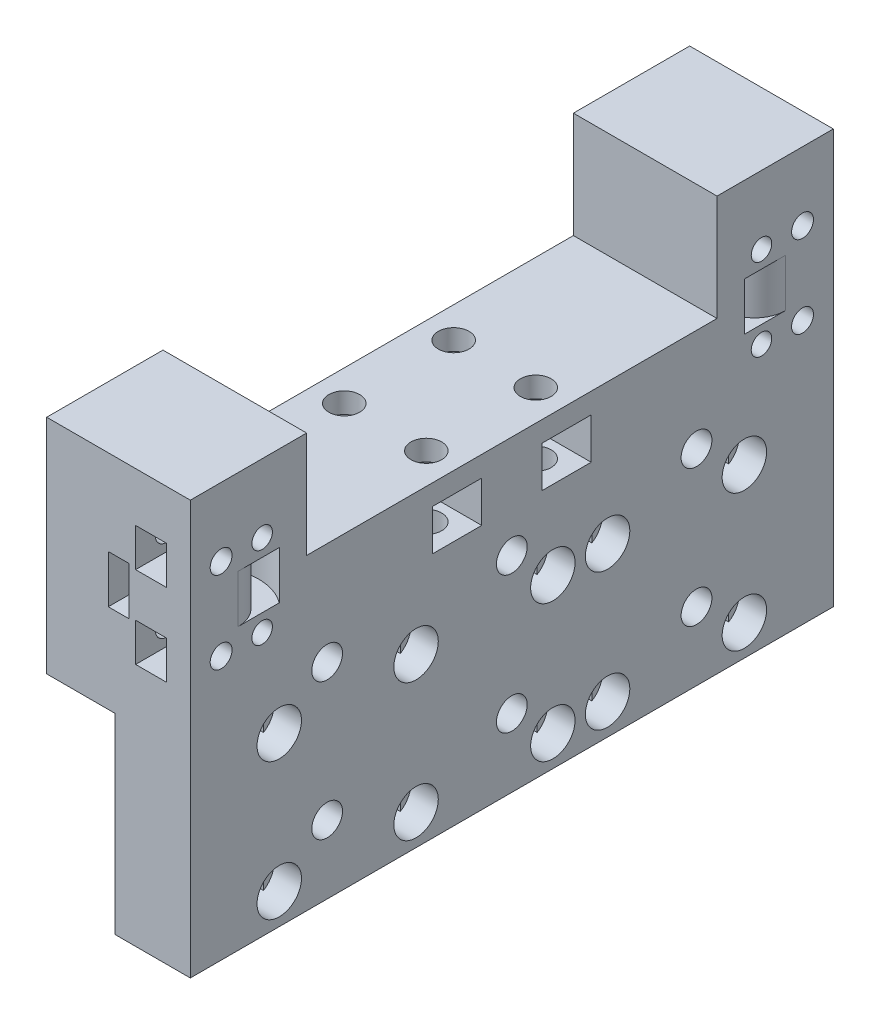
SolidWorks part; units mm, degrees
material "3D printed plastic"
ref_plane "Front Plane" through (0, 0, 0) normal (0, 0, 1) x (1, 0, 0)
ref_plane "Top Plane" through (0, 0, 0) normal (0, 1, 0) x (1, 0, 0)
ref_plane "Right Plane" through (0, 0, 0) normal (1, 0, 0) x (0, 0, -1)
sketch "Sketch1" plane through (0, 0, 0) normal (0, 0, 1) x (1, 0, 0)
  line L1 (0, 0) -> (11, 0)
  line L2 (0, 0) -> (0, 28)
  line L4 (11, 0) -> (11, 60.5)
  line L5 (0, 28) -> (-10, 28)
  line L7 (11, 60.5) -> (-10, 60.5)
  line L8 (-10, 28) -> (-10, 60.5)
  dimension "D1" = 28
  dimension "D2" = 10
  dimension "D4" = 32.5
  dimension "D6" = 11
extrude "Boss-Extrude1" add sketch "Sketch1" along normal mid plane 94
hole_wizard "CBORE for M3 Hex Socket Head Cap Screw1" positions "Sketch3" profile "Sketch2" counterbore size "M3" standard "DIN" end condition through all
sketch "Sketch3" plane through (11, 0, 0) normal (1, 0, 0) x (0, 0, -1)
  line L0 (-34, 24.5) -> (-34, 4.5) construction
  line L1 (-34, 4.5) -> (-14, 4.5) construction
  line L2 (-14, 4.5) -> (-14, 24.5) construction
  line L3 (-14, 24.5) -> (-34, 24.5) construction
  line L5 (0, 0) -> (0, 16.7465) construction
  line L7 (14, 24.5) -> (34, 24.5) construction
  line L8 (14, 4.5) -> (14, 24.5) construction
  line L9 (34, 4.5) -> (14, 4.5) construction
  line L10 (34, 24.5) -> (34, 4.5) construction
  line L11 (-34, 14.5) -> (-14, 14.5) construction
  line L16 (-24, 14.5) -> (-24, 4.5) construction
  line L19 (-47, 0) -> (47, 0) construction
  line L20 (6, 24.5) -> (-14, 24.5) construction
  line L22 (6, 24.5) -> (6, 4.5) construction
  line L23 (6, 4.5) -> (-14, 4.5) construction
  point P0 (-34, 4.5)
  point P2 (-34, 24.5)
  point P4 (-14, 24.5)
  point P6 (-14, 4.5)
  point P21 (14, 24.5)
  point P22 (34, 24.5)
  point P23 (14, 4.5)
  point P24 (34, 4.5)
  point P48 (6, 24.5)
  point P50 (6, 4.5)
  dimension "D1" = 20
  dimension "D2" = 48
  dimension "D3" = 14.5
sketch "Sketch2" plane through (11, 4.5, 34) normal (0, 1, 0) x (0, 0, -1)
  line L0 (0, 0) -> (0, 21)
  line L1 (0, 21) -> (1.7, 21)
  line L3 (1.7, 21) -> (1.7, 4)
  line L4 (1.7, 4) -> (3.25, 4)
  line L5 (3.25, 4) -> (3.25, 0)
  line L7 (3.25, 0) -> (0, 0)
  line L11 (0, -6.35) -> (0, 107.95) construction
  dimension "Thru Hole Dia." = 3.4
  dimension "Thru Hole Depth" = 21
  dimension "C'Bore Dia." = 6.5
  dimension "C'Bore Depth" = 4
sketch "Sketch4" plane through (0, 0, 47) normal (0, 0, 1) x (1, 0, 0)
  line L0 (11, 0) -> (11, 60.5) construction
  line L1 (-1, 48) -> (2, 48)
  line L2 (-1, 48) -> (-1, 41)
  line L3 (-1, 41) -> (2, 41)
  line L4 (2, 48) -> (2, 41)
  line L5 (-10, 28) -> (0, 28) construction
  line L6 (-1, 48) -> (2, 41) construction
  line L7 (0.5, 44.5) -> (0.5, 41) construction
  dimension "D1" = 7
  dimension "D2" = 3
  dimension "D3" = 9
  dimension "D4" = 13
ref_plane "Plane1" through (0, 44.5, 0) normal (0, 1, 0) x (1, 0, 0)
sketch "Sketch7" plane through (0, 44.5, 0) normal (0, 1, 0) x (1, 0, 0)
  line L0 (0.5, -47) -> (0.5, -40)
  line L1 (-1, -47) -> (2, -47) construction
  line L2 (12.5, -40) -> (6.5, -40) construction
  arc A1 (0.5, -40) -> (12.5, -40) centre (6.5, -40) cw
  dimension "D1" = 1.5
  dimension "D2" = 7
sweep "Cut-Sweep1" cut profiles "Sketch4" path "Sketch7"
sketch "Sketch8" plane through (11, 0, 0) normal (1, 0, 0) x (0, 0, -1)
  line L0 (-42.5, 38.5) -> (-42.5, 50.5) construction
  line L1 (-42.5, 44.5) -> (-40, 44.5) construction
  line L2 (-40, 41) -> (-40, 48) construction
  line L3 (-47, 0) -> (-47, 60.5) construction
  circle A0 centre (-42.5, 50.5) radius 1.6
  circle A1 centre (-42.5, 38.5) radius 1.6
  dimension "D1" = 12
  dimension "D2" = 3.2
  dimension "D3" = 4.5
extrude "Cut-Extrude1" cut sketch "Sketch8" against normal blind 12
sketch "Sketch10" plane through (11, 0, 0) normal (1, 0, 0) x (0, 0, -1)
  line L0 (-44.1166, 41.3) -> (-47, 41.3)
  line L1 (-47, 44.5) -> (-41.3484, 44.5) construction
  line L2 (-44.1166, 47.7) -> (-45.7332, 50.5) construction
  line L3 (-39.2668, 50.5) -> (-40.8834, 47.7) construction
  line L4 (-40.8834, 53.3) -> (-39.2668, 50.5) construction
  line L5 (-45.7332, 50.5) -> (-44.1166, 53.3) construction
  line L6 (-40.4834, 47.7) -> (-40.8834, 47.7)
  line L7 (-45.7332, 38.5) -> (-44.1166, 35.7) construction
  line L8 (-44.1166, 35.7) -> (-40.8834, 35.7)
  line L9 (-40.8834, 35.7) -> (-39.2668, 38.5) construction
  line L10 (-39.2668, 38.5) -> (-40.8834, 41.3) construction
  line L11 (-40.8834, 41.3) -> (-44.1166, 41.3)
  line L12 (-44.1166, 41.3) -> (-45.7332, 38.5) construction
  line L13 (-47, 0) -> (-47, 60.5) construction
  line L14 (-47, 41.3) -> (-47, 35.7)
  line L15 (-47, 35.7) -> (-44.1166, 35.7)
  line L16 (-40.8834, 35.7) -> (-40.4834, 35.7)
  line L17 (-40.4834, 35.7) -> (-38.8668, 38.5)
  line L18 (-38.8668, 38.5) -> (-40.4834, 41.3)
  line L19 (-40.4834, 41.3) -> (-40.8834, 41.3)
  line L20 (-38.8668, 50.5) -> (-40.4834, 47.7)
  line L21 (-40.4834, 53.3) -> (-38.8668, 50.5)
  line L22 (-40.8834, 53.3) -> (-40.4834, 53.3)
  line L23 (-47, 53.3) -> (-44.1166, 53.3)
  line L24 (-47, 47.7) -> (-47, 53.3)
  line L25 (-40.8834, 47.7) -> (-44.1166, 47.7)
  line L26 (-44.1166, 53.3) -> (-40.8834, 53.3)
  line L27 (-44.1166, 47.7) -> (-47, 47.7)
  circle A0 centre (-42.5, 50.5) radius 2.8 construction
  circle A1 centre (-42.5, 38.5) radius 2.8 construction
  dimension "D1" = 5.6
  dimension "D2" = 0.4
extrude "Cut-Extrude2" cut sketch "Sketch10" against normal blind 4.5 from offset 3.5 offset against normal yes
mirror "Mirror1" about plane through (0, 0, 0) normal (0, 0, 1) of "Cut-Extrude2", "Cut-Extrude1", "Cut-Sweep1"
sketch "Sketch11" plane through (11, 0, 0) normal (1, 0, 0) x (0, 0, -1)
  line L0 (-47, 60.5) -> (47, 60.5) construction
  line L1 (-30, 60.5) -> (30, 60.5)
  line L2 (-30, 60.5) -> (-30, 45)
  line L3 (-30, 45) -> (30, 45)
  line L4 (30, 60.5) -> (30, 45)
  line L5 (0, 60.5) -> (0, 0) construction
  line L6 (-47, 0) -> (47, 0) construction
  dimension "D1" = 60
  dimension "D2" = 45
extrude "Cut-Extrude3" cut sketch "Sketch11" against normal through all
sketch "Sketch12" plane through (11, 0, 0) normal (1, 0, 0) x (0, 0, -1)
  line L0 (0, 0) -> (0, 26.2706) construction
  line L1 (-47, 0) -> (47, 0) construction
  line L2 (-36.5, 50.5) -> (-36.5, 38.5) construction
  line L3 (-42.5, 50.5) -> (-42.5, 38.5) construction
  line L4 (-42.5, 44.5) -> (-36.5, 44.5) construction
  circle A0 centre (-36.5, 50.5) radius 1.5
  circle A1 centre (-36.5, 38.5) radius 1.5
  circle A2 centre (36.5, 38.5) radius 1.5
  circle A3 centre (36.5, 50.5) radius 1.5
  dimension "D1" = 12
  dimension "D2" = 3
  dimension "D3" = 4.5
extrude "Cut-Extrude4" cut sketch "Sketch12" against normal blind 8
sketch "Sketch13" plane through (0, 45, 0) normal (0, 1, 0) x (1, 0, 0)
  line L0 (-5.5, 8) -> (-5.5, -8) construction
  line L1 (-5.5, -8) -> (6.5, -8) construction
  line L2 (6.5, -8) -> (6.5, 8) construction
  line L3 (6.5, 8) -> (-5.5, 8) construction
  line L4 (-5.5, 8) -> (6.5, -8) construction
  line L5 (11, 0) -> (6.5, 0) construction
  line L6 (11, -30) -> (11, 30) construction
  line L7 (-5.5, 0) -> (-10, 0) construction
  line L8 (-10, -30) -> (-10, 30) construction
  circle A0 centre (-5.5, 8) radius 2.25
  circle A1 centre (6.5, 8) radius 2.25
  circle A2 centre (6.5, -8) radius 2.25
  circle A3 centre (-5.5, -8) radius 2.25
  dimension "D2" = 4.5
  dimension "D1" = 12
  dimension "D3" = 16
extrude "Cut-Extrude5" cut sketch "Sketch13" against normal blind 14
sketch "Sketch14" plane through (0, 45, 0) normal (0, 1, 0) x (1, 0, 0)
  line L0 (-7.5785, 11.6) -> (-10, 11.6)
  line L1 (-9.6569, 8) -> (-7.5785, 4.4) construction
  line L2 (-7.5785, 4.4) -> (-3.4215, 4.4)
  line L3 (-3.4215, 4.4) -> (-1.3431, 8)
  line L4 (-1.3431, 8) -> (-3.4215, 11.6)
  line L5 (-3.4215, 11.6) -> (-7.5785, 11.6)
  line L6 (-7.5785, 11.6) -> (-9.6569, 8) construction
  line L7 (-10, -30) -> (-10, 30) construction
  line L8 (-10, 11.6) -> (-10, 4.4)
  line L9 (-10, 4.4) -> (-7.5785, 4.4)
  line L10 (-5.5, 8) -> (-5.5, -8) construction
  line L11 (-5.5, 0) -> (6.5, 0) construction
  line L12 (6.5, 8) -> (6.5, -8) construction
  line L14 (0.5, -5.0794) -> (0.5, 5.0794) construction
  line L15 (6.5, 8) -> (6.5, -8) construction
  line L16 (8.5785, 11.6) -> (10.6569, 8) construction
  line L17 (10.6569, 8) -> (8.5785, 4.4) construction
  line L18 (11, 4.4) -> (8.5785, 4.4)
  line L19 (11, 11.6) -> (11, 4.4)
  line L20 (4.4215, 11.6) -> (8.5785, 11.6)
  line L21 (2.3431, 8) -> (4.4215, 11.6)
  line L22 (4.4215, 4.4) -> (2.3431, 8)
  line L23 (8.5785, 4.4) -> (4.4215, 4.4)
  line L24 (8.5785, 11.6) -> (11, 11.6)
  line L25 (10.6569, -8) -> (8.5785, -4.4) construction
  line L26 (8.5785, -11.6) -> (10.6569, -8) construction
  line L27 (-7.5785, -11.6) -> (-9.6569, -8) construction
  line L28 (-9.6569, -8) -> (-7.5785, -4.4) construction
  line L29 (8.5785, -11.6) -> (11, -11.6)
  line L30 (8.5785, -4.4) -> (4.4215, -4.4)
  line L31 (4.4215, -4.4) -> (2.3431, -8)
  line L32 (2.3431, -8) -> (4.4215, -11.6)
  line L33 (4.4215, -11.6) -> (8.5785, -11.6)
  line L34 (11, -11.6) -> (11, -4.4)
  line L35 (11, -4.4) -> (8.5785, -4.4)
  line L36 (-10, -4.4) -> (-7.5785, -4.4)
  line L37 (-10, -11.6) -> (-10, -4.4)
  line L38 (-3.4215, -11.6) -> (-7.5785, -11.6)
  line L39 (-1.3431, -8) -> (-3.4215, -11.6)
  line L40 (-3.4215, -4.4) -> (-1.3431, -8)
  line L41 (-7.5785, -4.4) -> (-3.4215, -4.4)
  line L42 (-7.5785, -11.6) -> (-10, -11.6)
  circle A0 centre (-5.5, 8) radius 3.6 construction
  circle A1 centre (6.5, 8) radius 3.6 construction
  circle A2 centre (6.5, -8) radius 3.6 construction
  circle A3 centre (-5.5, -8) radius 3.6 construction
  point P39 (0.5, 0)
  dimension "D1" = 7.2
extrude "Cut-Extrude6" cut sketch "Sketch14" against normal blind 6 from offset 3 offset against normal yes
sketch "Sketch15" plane through (11, 0, 0) normal (1, 0, 0) x (0, 0, -1)
  line L0 (0, 30) -> (0, 10) construction
  line L1 (0, 10) -> (-27, 10) construction
  line L2 (-27, 10) -> (-27, 30) construction
  line L3 (-27, 30) -> (0, 30) construction
  line L4 (0, 10) -> (0, 0) construction
  line L6 (-27, 24.5) -> (-27, 30) construction
  circle A0 centre (-27, 30) radius 2.25
  circle A1 centre (-27, 10) radius 2.25
  circle A2 centre (0, 10) radius 2.25
  circle A3 centre (0, 30) radius 2.25
  circle A4 centre (27, 10) radius 2.25
  circle A5 centre (27, 30) radius 2.25
  dimension "D1" = 4.5
  dimension "D4" = 54
  dimension "D2" = 10
  dimension "D3" = 20
extrude "Cut-Extrude7" cut sketch "Sketch15" against normal through all
sketch "Sketch16" plane through (11, 0, 0) normal (1, 0, 0) x (0, 0, -1)
  line L1 (-27, 25.9008) -> (-23.45, 27.9504)
  line L2 (-23.45, 27.9504) -> (-23.45, 32.0496)
  line L3 (-23.45, 32.0496) -> (-27, 34.0992)
  line L4 (-27, 34.0992) -> (-30.55, 32.0496)
  line L5 (-30.55, 32.0496) -> (-30.55, 27.9504)
  line L6 (-30.55, 27.9504) -> (-27, 25.9008)
  line L7 (-27, 5.9008) -> (-23.45, 7.9504)
  line L8 (-23.45, 7.9504) -> (-23.45, 12.0496)
  line L9 (-23.45, 12.0496) -> (-27, 14.0992)
  line L10 (-27, 14.0992) -> (-30.55, 12.0496)
  line L11 (-30.55, 12.0496) -> (-30.55, 7.9504)
  line L12 (-30.55, 7.9504) -> (-27, 5.9008)
  line L13 (0, 25.9008) -> (3.55, 27.9504)
  line L14 (3.55, 27.9504) -> (3.55, 32.0496)
  line L15 (3.55, 32.0496) -> (0, 34.0992)
  line L16 (0, 34.0992) -> (-3.55, 32.0496)
  line L17 (-3.55, 32.0496) -> (-3.55, 27.9504)
  line L18 (-3.55, 27.9504) -> (0, 25.9008)
  line L19 (0, 14.0992) -> (-3.55, 12.0496)
  line L20 (-3.55, 12.0496) -> (-3.55, 7.9504)
  line L21 (-3.55, 7.9504) -> (0, 5.9008)
  line L22 (0, 5.9008) -> (3.55, 7.9504)
  line L23 (3.55, 7.9504) -> (3.55, 12.0496)
  line L24 (3.55, 12.0496) -> (0, 14.0992)
  line L25 (27, 25.9008) -> (30.55, 27.9504)
  line L26 (30.55, 27.9504) -> (30.55, 32.0496)
  line L27 (30.55, 32.0496) -> (27, 34.0992)
  line L28 (27, 34.0992) -> (23.45, 32.0496)
  line L29 (23.45, 32.0496) -> (23.45, 27.9504)
  line L30 (23.45, 27.9504) -> (27, 25.9008)
  line L31 (27, 14.0992) -> (23.45, 12.0496)
  line L32 (23.45, 12.0496) -> (23.45, 7.9504)
  line L33 (23.45, 7.9504) -> (27, 5.9008)
  line L34 (27, 5.9008) -> (30.55, 7.9504)
  line L35 (30.55, 7.9504) -> (30.55, 12.0496)
  line L36 (30.55, 12.0496) -> (27, 14.0992)
  circle A0 centre (-27, 30) radius 3.55 construction
  circle A1 centre (-27, 10) radius 3.55 construction
  circle A2 centre (0, 30) radius 3.55 construction
  circle A3 centre (0, 10) radius 3.55 construction
  circle A4 centre (27, 30) radius 3.55 construction
  circle A5 centre (27, 10) radius 3.55 construction
  dimension "D1" = 7.1
extrude "Cut-Extrude8" cut sketch "Sketch16" against normal through all from offset 4 offset against normal yes
sketch "Sketch17" plane through (7, 0, 0) normal (1, 0, 0) x (0, 0, -1)
  line L0 (-35.7, 27.2699) -> (-35.7, 21.7301)
  line L1 (-32.3, 27.2699) -> (-32.3, 21.7301)
  line L2 (0, 0) -> (0, 20.8915) construction
  line L3 (-15.7, 27.2699) -> (-15.7, 21.7301)
  line L4 (-12.3, 27.2699) -> (-12.3, 21.7301)
  line L5 (-15.7, 7.2699) -> (-15.7, 1.7301)
  line L6 (-12.3, 7.2699) -> (-12.3, 1.7301)
  line L7 (-35.7, 7.2699) -> (-35.7, 1.7301)
  line L8 (-32.3, 7.2699) -> (-32.3, 1.7301)
  line L9 (32.3, 7.2699) -> (32.3, 1.7301)
  line L10 (35.7, 7.2699) -> (35.7, 1.7301)
  line L11 (12.3, 7.2699) -> (12.3, 1.7301)
  line L12 (15.7, 7.2699) -> (15.7, 1.7301)
  line L13 (12.3, 27.2699) -> (12.3, 21.7301)
  line L14 (15.7, 27.2699) -> (15.7, 21.7301)
  line L15 (32.3, 27.2699) -> (32.3, 21.7301)
  line L16 (35.7, 27.2699) -> (35.7, 21.7301)
  line L17 (4.3, 27.2699) -> (4.3, 21.7301)
  line L18 (7.7, 27.2699) -> (7.7, 21.7301)
  line L19 (4.3, 7.2699) -> (4.3, 1.7301)
  line L20 (7.7, 7.2699) -> (7.7, 1.7301)
  arc A0 (-32.3, 27.2699) -> (-35.7, 27.2699) centre (-34, 24.5) ccw
  circle A1 centre (-34, 24.5) radius 3.25 construction
  arc A2 (-35.7, 21.7301) -> (-32.3, 21.7301) centre (-34, 24.5) ccw
  circle A3 centre (-34, 24.5) radius 1.7 construction
  arc A4 (-12.3, 27.2699) -> (-15.7, 27.2699) centre (-14, 24.5) ccw
  arc A5 (-15.7, 21.7301) -> (-12.3, 21.7301) centre (-14, 24.5) ccw
  arc A6 (-12.3, 7.2699) -> (-15.7, 7.2699) centre (-14, 4.5) ccw
  arc A7 (-15.7, 1.7301) -> (-12.3, 1.7301) centre (-14, 4.5) ccw
  arc A8 (-32.3, 7.2699) -> (-35.7, 7.2699) centre (-34, 4.5) ccw
  arc A9 (-35.7, 1.7301) -> (-32.3, 1.7301) centre (-34, 4.5) ccw
  arc A10 (35.7, 1.7301) -> (32.3, 1.7301) centre (34, 4.5) cw
  arc A11 (32.3, 7.2699) -> (35.7, 7.2699) centre (34, 4.5) cw
  arc A12 (15.7, 1.7301) -> (12.3, 1.7301) centre (14, 4.5) cw
  arc A13 (12.3, 7.2699) -> (15.7, 7.2699) centre (14, 4.5) cw
  arc A14 (15.7, 21.7301) -> (12.3, 21.7301) centre (14, 24.5) cw
  arc A15 (12.3, 27.2699) -> (15.7, 27.2699) centre (14, 24.5) cw
  arc A16 (35.7, 21.7301) -> (32.3, 21.7301) centre (34, 24.5) cw
  arc A17 (32.3, 27.2699) -> (35.7, 27.2699) centre (34, 24.5) cw
  arc A18 (7.7, 27.2699) -> (4.3, 27.2699) centre (6, 24.5) ccw
  arc A19 (4.3, 21.7301) -> (7.7, 21.7301) centre (6, 24.5) ccw
  arc A20 (7.7, 7.2699) -> (4.3, 7.2699) centre (6, 4.5) ccw
  arc A21 (4.3, 1.7301) -> (7.7, 1.7301) centre (6, 4.5) ccw
  dimension "D1" = 2
  dimension "D2" = 2
  dimension "D3" = 2
extrude "Cut-Extrude9" cut sketch "Sketch17" against normal blind 0.5
